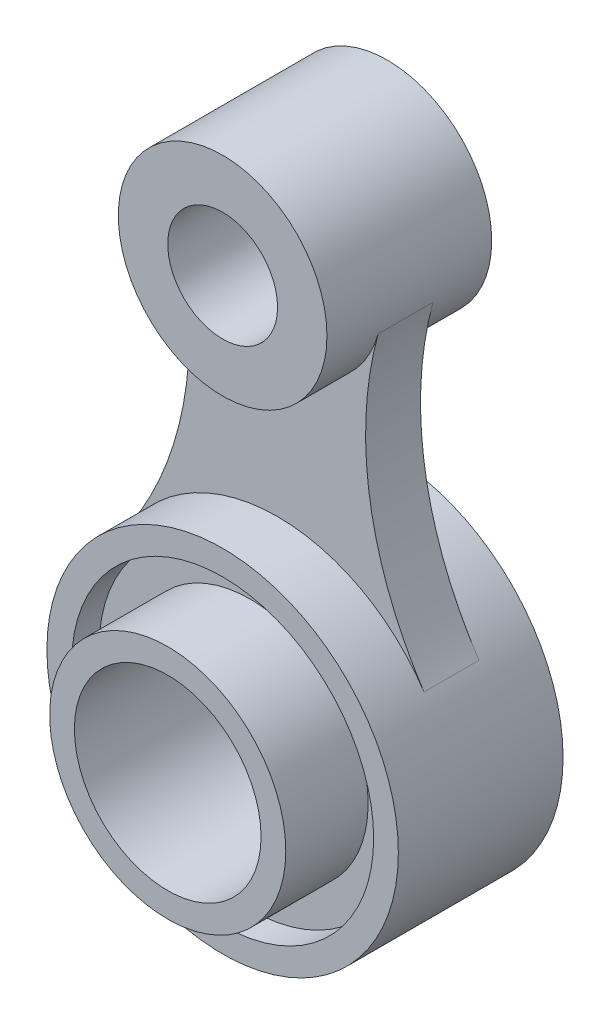
SolidWorks part; units mm, degrees
ref_plane "Front Plane" through (0, 0, 0) normal (0, 0, 1) x (1, 0, 0)
ref_plane "Top Plane" through (0, 0, 0) normal (0, 1, 0) x (1, 0, 0)
ref_plane "Right Plane" through (0, 0, 0) normal (1, 0, 0) x (0, 0, -1)
sketch "Sketch2" plane through (0, 0, 0) normal (0, 0, 1) x (1, 0, 0)
  circle A0 centre (0, 0) radius 27.5
  circle A1 centre (0, 0) radius 32
extrude "Boss-Extrude1" add sketch "Sketch2" along normal blind 30
ref_plane "Plane1" through (0, 0, 15) normal (0, 0, 1) x (1, 0, 0)
sketch "Sketch3" plane through (0, 0, 15) normal (0, 0, 1) x (1, 0, 0)
  line L0 (0, 0) -> (0, 75) construction
  arc A0 (-18.3212, 69.9669) -> (18.3212, 69.9669) centre (0, 75) ccw
  circle A1 centre (0, 0) radius 32 construction
  arc A2 (-26.6783, 17.6711) -> (-18.3212, 69.9669) centre (-80.0349, 53.0133) ccw
  arc A3 (26.6783, 17.6711) -> (-26.6783, 17.6711) centre (0, 0) ccw
  arc A4 (26.6783, 17.6711) -> (18.3212, 69.9669) centre (80.0349, 53.0133) cw
  dimension "D1" = 75
extrude "Boss-Extrude2" add sketch "Sketch3" along normal blind 5 and the other way blind 5
sketch "Sketch4" plane through (0, 0, 15) normal (0, 0, 1) x (1, 0, 0)
  circle A0 centre (0, 75) radius 19
  circle A1 centre (0, 75) radius 10
extrude "Boss-Extrude3" add sketch "Sketch4" along normal blind 15 and the other way blind 15
sketch "Sketch5" plane through (0, 0, 15) normal (0, 0, 1) x (1, 0, 0)
  circle A0 centre (0, 0) radius 27.5
extrude "Boss-Extrude4" add sketch "Sketch5" along normal blind 10 and the other way blind 15
sketch "Sketch6" plane through (0, 0, 25) normal (0, 0, 1) x (1, 0, 0)
  circle A0 centre (0, 0) radius 21.5
extrude "Boss-Extrude5" add sketch "Sketch6" along normal blind 15
sketch "Sketch7" plane through (0, 0, 40) normal (0, 0, 1) x (1, 0, 0)
  circle A0 centre (0, 0) radius 17
extrude "Cut-Extrude1" cut sketch "Sketch7" against normal up to surface (40 mm away) up to face at (32, 0, 0)
